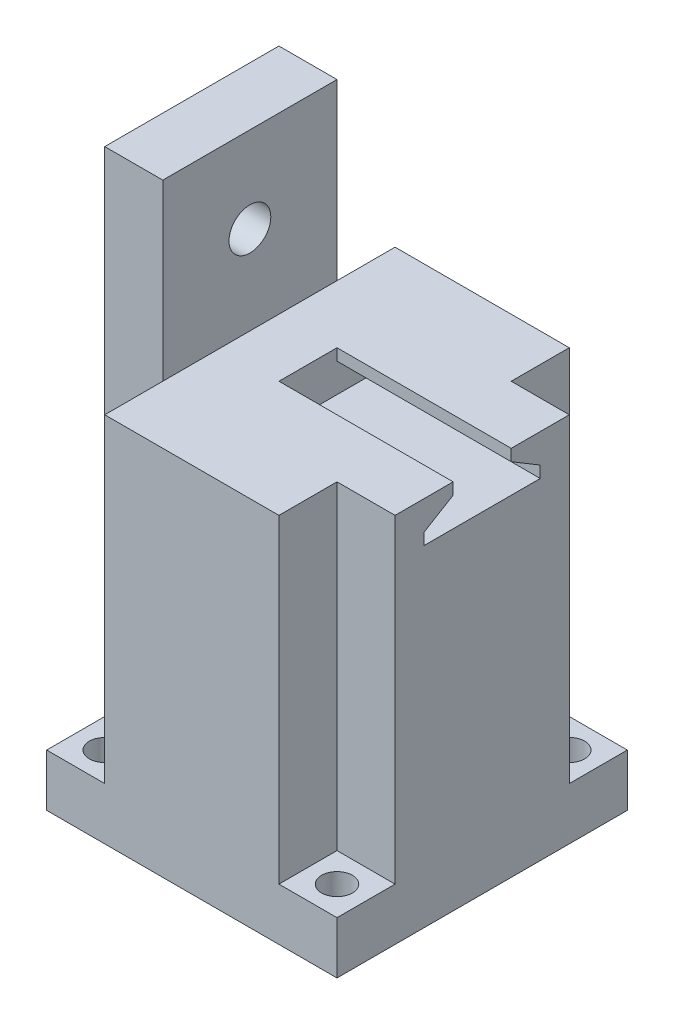
SolidWorks part; units mm, degrees
ref_plane "Front Plane" through (0, 0, 0) normal (0, 0, 1) x (1, 0, 0)
ref_plane "Top Plane" through (0, 0, 0) normal (0, 1, 0) x (1, 0, 0)
ref_plane "Right Plane" through (0, 0, 0) normal (1, 0, 0) x (0, 0, -1)
sketch "Sketch1" plane through (0, 0, 0) normal (0, 1, 0) x (1, 0, 0)
  line L1 (-25, -25) -> (25, -25)
  line L2 (-25, -25) -> (-25, 25)
  line L3 (-25, 25) -> (25, 25)
  line L4 (25, -25) -> (25, 25)
  line L5 (-25, -25) -> (25, 25) construction
  line L6 (-25, 25) -> (25, -25) construction
  point P0 (0, 0)
  dimension "D1" = 50
  dimension "D2" = 50
extrude "Boss-Extrude1" add sketch "Sketch1" along normal blind 64
sketch "Sketch2" plane through (0, 64, 0) normal (0, 1, 0) x (1, 0, 0)
  line L0 (25, 25) -> (15, 25)
  line L1 (-25, 25) -> (-15, 25)
  line L2 (-25, 25) -> (-25, 15)
  line L3 (-25, 15) -> (-15, 15)
  line L4 (-15, 25) -> (-15, 15)
  line L5 (25, 25) -> (25, 15)
  line L6 (25, 15) -> (15, 15)
  line L7 (15, 25) -> (15, 15)
  line L8 (25, -25) -> (25, -15)
  line L9 (25, -25) -> (15, -25)
  line L10 (15, -25) -> (15, -15)
  line L11 (25, -15) -> (15, -15)
  line L12 (-25, -25) -> (-15, -25)
  line L13 (-25, -25) -> (-25, -15)
  line L14 (-25, -15) -> (-15, -15)
  line L15 (-15, -25) -> (-15, -15)
  point P20 (0, 0)
  dimension "D1" = 10
  dimension "D2" = 10
  dimension "D3" = 4
extrude "Cut-Extrude1" cut sketch "Sketch2" against normal blind 55
sketch "Sketch3" plane through (25, 0, 0) normal (1, 0, 0) x (0, 0, -1)
  line L0 (0, 0) -> (0, 64) construction
  line L1 (-15, 64) -> (15, 64) construction
  line L2 (-5, 64) -> (5, 64)
  line L3 (5, 64) -> (5, 62)
  line L4 (5, 62) -> (10, 59)
  line L5 (10, 59) -> (10, 57)
  line L6 (10, 57) -> (-10, 57)
  line L7 (-10, 59) -> (-10, 57)
  line L8 (-5, 62) -> (-10, 59)
  line L9 (-5, 64) -> (-5, 62)
  point P11 (0, 57)
  dimension "D1" = 5
  dimension "D2" = 10
  dimension "D3" = 2
  dimension "D4" = 2
  dimension "D5" = 7
extrude "Cut-Extrude2" cut sketch "Sketch3" against normal blind 30
sketch "Sketch4" plane through (0, 64, 0) normal (0, 1, 0) x (1, 0, 0)
  line L1 (-25, 15) -> (-15, 15)
  line L2 (-25, 15) -> (-25, -15)
  line L3 (-25, -15) -> (-15, -15)
  line L4 (-15, 15) -> (-15, -15)
extrude "Boss-Extrude2" add sketch "Sketch4" along normal blind 30
sketch "Sketch6" plane through (0, 0, 0) normal (0, -1, 0) x (1, 0, 0)
  line L0 (12.5, -12.5) -> (-12.5, -12.5)
  line L1 (-12.5, -12.5) -> (12.5, -12.5)
  line L2 (-12.5, -12.5) -> (-12.5, 12.5)
  line L3 (-12.5, 12.5) -> (12.5, 12.5)
  line L4 (12.5, -12.5) -> (12.5, 12.5)
  line L5 (-12.5, -12.5) -> (12.5, 12.5) construction
  line L6 (-12.5, 12.5) -> (12.5, -12.5) construction
  line L7 (12.5, 12.5) -> (20.5, 12.5)
  line L8 (12.5, 12.5) -> (12.5, -12.5)
  line L9 (12.5, -12.5) -> (20.5, -12.5)
  line L10 (20.5, 12.5) -> (20.5, -12.5)
  line L11 (12.5, -12.5) -> (12.5, -20.5)
  line L12 (12.5, -20.5) -> (-12.5, -20.5)
  line L13 (-12.5, -12.5) -> (-12.5, -20.5)
  line L14 (-12.5, -12.5) -> (-12.5, 12.5)
  line L15 (-12.5, -12.5) -> (-20.5, -12.5)
  line L16 (-20.5, -12.5) -> (-20.5, 12.5)
  line L17 (-12.5, 12.5) -> (-20.5, 12.5)
  line L18 (-12.5, 12.5) -> (12.5, 12.5)
  line L19 (-12.5, 12.5) -> (-12.5, 20.5)
  line L20 (-12.5, 20.5) -> (12.5, 20.5)
  line L21 (12.5, 12.5) -> (12.5, 20.5)
  point P0 (0, 0)
  point P23 (0, 0)
  dimension "D1" = 25
  dimension "D2" = 25
  dimension "D3" = 8
  dimension "D4" = 4
extrude "Cut-Extrude4" cut sketch "Sketch6" against normal blind 50 contours L2 L17 L16 L15 | L3 L21 L20 L19 | L0 L4 L3 L2 | L10 L7 L4 L9 | L0 L13 L12 L11
sketch "Sketch7" plane through (-15, 0, 0) normal (1, 0, 0) x (0, 0, -1)
  circle A0 centre (0, 79.2212) radius 3.6
  dimension "D1" = 7.2
extrude "Cut-Extrude5" cut sketch "Sketch7" against normal blind 50
sketch "Sketch8" plane through (0, 9, 0) normal (0, 1, 0) x (1, 0, 0)
  line L0 (15, -15) -> (25, -25) construction
  circle A0 centre (20, -20) radius 2.65
  circle A1 centre (-20, -20) radius 2.65
  circle A2 centre (-20, 20) radius 2.65
  circle A3 centre (20, 20) radius 2.65
  point P15 (0, 0)
  dimension "D1" = 5.3
  dimension "D2" = 4
extrude "Cut-Extrude6" cut sketch "Sketch8" against normal blind 50
